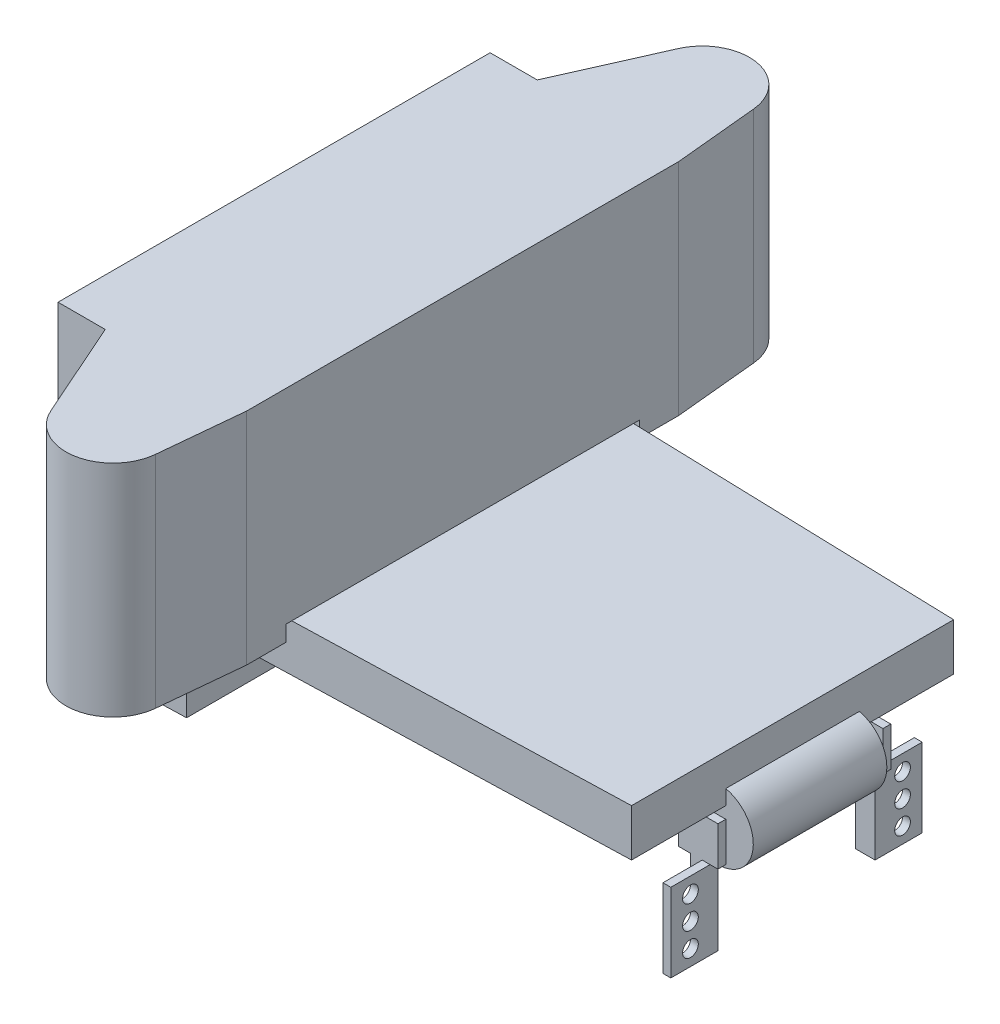
SolidWorks part; units mm, degrees
ref_plane "Front" through (0, 0, 0) normal (0, 0, 1) x (1, 0, 0)
ref_plane "Top" through (0, 0, 0) normal (0, 1, 0) x (1, 0, 0)
ref_plane "Right" through (0, 0, 0) normal (1, 0, 0) x (0, 0, -1)
sketch "Эскиз1" plane through (0, 0, 0) normal (0, 1, 0) x (1, 0, 0)
  line L0 (-81.1278, 0) -> (80.5852, 0) construction
  line L1 (-50, 0) -> (50, 0) construction
  line L2 (12, 27.5) -> (10.9719, 38.0803)
  line L3 (-12, 27.5) -> (12, 27.5)
  line L4 (-12, 27.5) -> (-12, -27.5)
  line L5 (-12, -27.5) -> (12, -27.5)
  line L6 (12, 27.5) -> (12, -27.5)
  line L7 (-12, 27.5) -> (12, -27.5) construction
  line L8 (-12, -27.5) -> (12, 27.5) construction
  line L9 (12, -27.5) -> (10.9719, -38.0803)
  line L10 (-0.4846, 39.933) -> (-6, 27.5)
  line L11 (-0.4846, -39.933) -> (-6, -27.5)
  circle A0 centre (5, 37.5) radius 6
  circle A1 centre (5, -37.5) radius 6
  point P5 (0, 0)
  dimension "D5" = 12
  dimension "D1" = 55
  dimension "D2" = 24
  dimension "D3" = 7
  dimension "D4" = 75
  dimension "D6" = 18
extrude "Бобышка-Вытянуть1" add sketch "Эскиз1" along normal blind 28 contours L6 L3 L4 L5 | A0 | A1 L9 L5 L11 | A1 | A0 L10 L3 L2
sketch "Эскиз2" plane through (0, 0, 0) normal (0, -1, 0) x (1, 0, 0)
  line L0 (12, 0) -> (-12, 0) construction
  line L1 (12, -27.5) -> (12, 27.5) construction
  line L2 (-12, -27.5) -> (-12, 27.5) construction
  line L4 (12, 22.5) -> (-6, 22.5)
  line L5 (12, 22.5) -> (12, -22.5)
  line L6 (12, -22.5) -> (-6, -22.5)
  line L7 (-6, 22.5) -> (-6, -22.5)
  dimension "D1" = 45
  dimension "D2" = 18
extrude "Вырез-Вытянуть1" cut sketch "Эскиз2" against normal blind 2
sketch "Эскиз3" plane through (0, 2, 0) normal (0, -1, 0) x (1, 0, 0)
  line L0 (12, 0) -> (75.8584, 0) construction
  line L1 (12, -22.5) -> (12, 22.5) construction
  line L2 (-4, 22.2262) -> (54, 20.5)
  line L3 (54, 20.5) -> (54, -20.5)
  line L4 (54, -20.5) -> (-4, -22.2262)
  line L5 (-4, -22.2262) -> (-4, 22.2262)
  point P7 (12, 21.75)
  point P10 (12, -21.75)
  dimension "D1" = 43.5
  dimension "D2" = 58
  dimension "D3" = 41
  dimension "D4" = 16
extrude "Бобышка-Вытянуть2" add sketch "Эскиз3" along normal blind 6 separate body
sketch "Эскиз4" plane through (0, -4, 0) normal (0, -1, 0) x (1, 0, 0)
  line L0 (-4, 22.2262) -> (-4, -22.2262)
  line L1 (-4, -22.2262) -> (-1, -22.1369)
  line L2 (-4, -22.2262) -> (54, -20.5) construction
  line L3 (-1, -22.1369) -> (-1, 22.1369)
  line L4 (54, 20.5) -> (-4, 22.2262) construction
  line L9 (-4, 22.2262) -> (-4, -22.2262)
  line L10 (-4, -22.2262) -> (54, -20.5)
  line L11 (54, -20.5) -> (54, 20.5)
  line L12 (54, 20.5) -> (-4, 22.2262)
  line L13 (-4, 22.2262) -> (-4, -22.2262)
  line L14 (-4, -22.2262) -> (54, -20.5)
  line L15 (54, -20.5) -> (54, 20.5)
  line L16 (54, 20.5) -> (-1, 22.1369)
  line M7 (-4, 22.2262) -> (-4, -22.2262)
  line M8 (-4, -22.2262) -> (54, -20.5)
  line M10 (54, 20.5) -> (-4, 22.2262)
  dimension "D1" = 3
  dimension "D2" = 0
extrude "Бобышка-Вытянуть3" add sketch "Эскиз4" along normal blind 11 contours L3 M8 M10 M7
sketch "Эскиз5" plane through (0, 0, 0) normal (0, 0, 1) x (1, 0, 0)
  line L0 (-1, -15) -> (-1, -4) construction
  line L1 (54, -4) -> (-1, -4) construction
  circle A0 centre (53, -6.5) radius 4.5
  dimension "D1" = 9
  dimension "D2" = 54
  dimension "D3" = 2.5
extrude "Бобышка-Вытянуть4" add sketch "Эскиз5" along normal mid plane 17
sketch "Эскиз7" plane through (0, 0, 0) normal (0, 0, 1) x (1, 0, 0)
  circle A0 centre (53, -6.5) radius 1
  dimension "D1" = 2
extrude "Бобышка-Вытянуть5" add sketch "Эскиз7" along normal mid plane 22
sketch "Эскиз8" plane through (0, 0, -8.5) normal (0, 0, -1) x (-1, 0, 0)
  line L5 (-54.5, -9) -> (-52, -9)
  line L6 (-54.5, -9) -> (-54.5, -19)
  line L7 (-54.5, -19) -> (-52, -19)
  line L8 (-52, -9) -> (-52, -19)
  line L9 (-50.5, -4) -> (-55.5, -4)
  line L10 (-50.5, -4) -> (-50.5, -9)
  line L11 (-50.5, -9) -> (-55.5, -9)
  line L12 (-55.5, -4) -> (-55.5, -9)
  line L13 (-50.5, -4) -> (-55.5, -9) construction
  line L14 (-50.5, -9) -> (-55.5, -4) construction
  point P8 (-53, -6.5)
  circle M12 centre (-53, -6.5) radius 1
  arc M13 (-54, -2.1125) -> (-49.2583, -4) centre (-53, -6.5) ccw
  line M14 (-49.2583, -4) -> (-54, -4)
  dimension "D1" = 5
  dimension "D2" = 5
  dimension "D3" = 2.5
  dimension "D4" = 1
  dimension "D5" = 10
extrude "Бобышка-Вытянуть6" add sketch "Эскиз8" along normal blind 1 from offset 1.5 contours L8 L5 L6 M13 | L9 L12 L11 L5 L10 M14 M12 | L8 L6 L7 M13
mirror "Зеркальное отражение1" about plane through (0, 0, 0) normal (0, 0, 1) of "Бобышка-Вытянуть6"
sketch "Эскиз9" plane through (0, 0, -11) normal (0, 0, -1) x (-1, 0, 0)
  line L0 (-54.5, -19) -> (-52, -19) construction
  line L1 (-54.5, -9) -> (-53.5, -9)
  line L2 (-54.5, -9) -> (-54.5, -19)
  line L3 (-54.5, -19) -> (-53.5, -19)
  line L4 (-53.5, -9) -> (-53.5, -19)
  dimension "D1" = 1
extrude "Бобышка-Вытянуть7" add sketch "Эскиз9" along normal blind 5
mirror "Зеркальное отражение2" about plane through (0, 0, 0) normal (0, 0, 1) of "Бобышка-Вытянуть7"
sketch "Эскиз10" plane through (54.5, 0, 0) normal (1, 0, 0) x (0, 0, -1)
  line L0 (0, 6.3724) -> (0, -22.586) construction
  line L1 (20.5, 2) -> (-20.5, 2) construction
  circle A0 centre (13.5, -11) radius 1
  circle A1 centre (13.5, -14) radius 1
  circle A2 centre (13.5, -17) radius 1
  dimension "D1" = 2
  dimension "D2" = 13.5
  dimension "D3" = 13
  dimension "D4" = 3
  dimension "D5" = 3
extrude "Вырез-Вытянуть2" cut sketch "Эскиз10" against normal up to surface (1 mm away) up to face at (53.5, -14, -13.5)
mirror "Зеркальное отражение3" about plane through (0, 0, 0) normal (0, 0, 1) of "Вырез-Вытянуть2"
